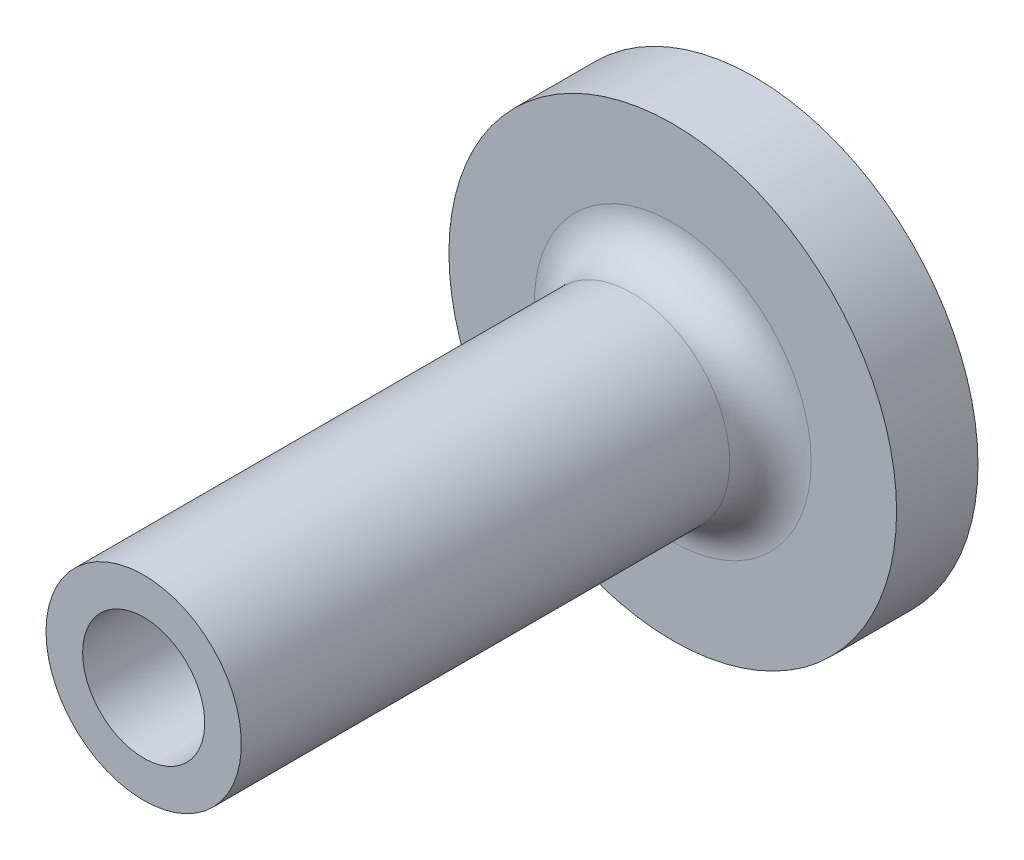
SolidWorks part; units mm, degrees
ref_plane "Plan de face" through (0, 0, 0) normal (0, 0, 1) x (1, 0, 0)
ref_plane "Plan de dessus" through (0, 0, 0) normal (0, 1, 0) x (1, 0, 0)
ref_plane "Plan de droite" through (0, 0, 0) normal (1, 0, 0) x (0, 0, -1)
sketch "Esquisse1" plane through (0, 0, 0) normal (0, 0, 1) x (1, 0, 0)
  circle A0 centre (0, 0) radius 5.5
  dimension "D1" = 11
extrude "Boss.-Extru.1" add sketch "Esquisse1" along normal blind 2
sketch "Esquisse2" plane through (0, 0, 2) normal (0, 0, 1) x (1, 0, 0)
  circle A0 centre (0, 0) radius 2.4
  circle A2 centre (0, 0) radius 1.5
  dimension "D1" = 4.8
  dimension "D2" = 3
extrude "Boss.-Extru.2" add sketch "Esquisse2" along normal blind 13
fillet "Congé1" radius 1 1 edges at (2.4, 0, 2)
sketch "Esquisse7" plane through (0, 0, 15) normal (0, 0, 1) x (1, 0, 0)
  circle A0 centre (0, 0) radius 3.1564
  circle A1 centre (0, 0) radius 2.6245
  dimension "D1" = 6.3129
